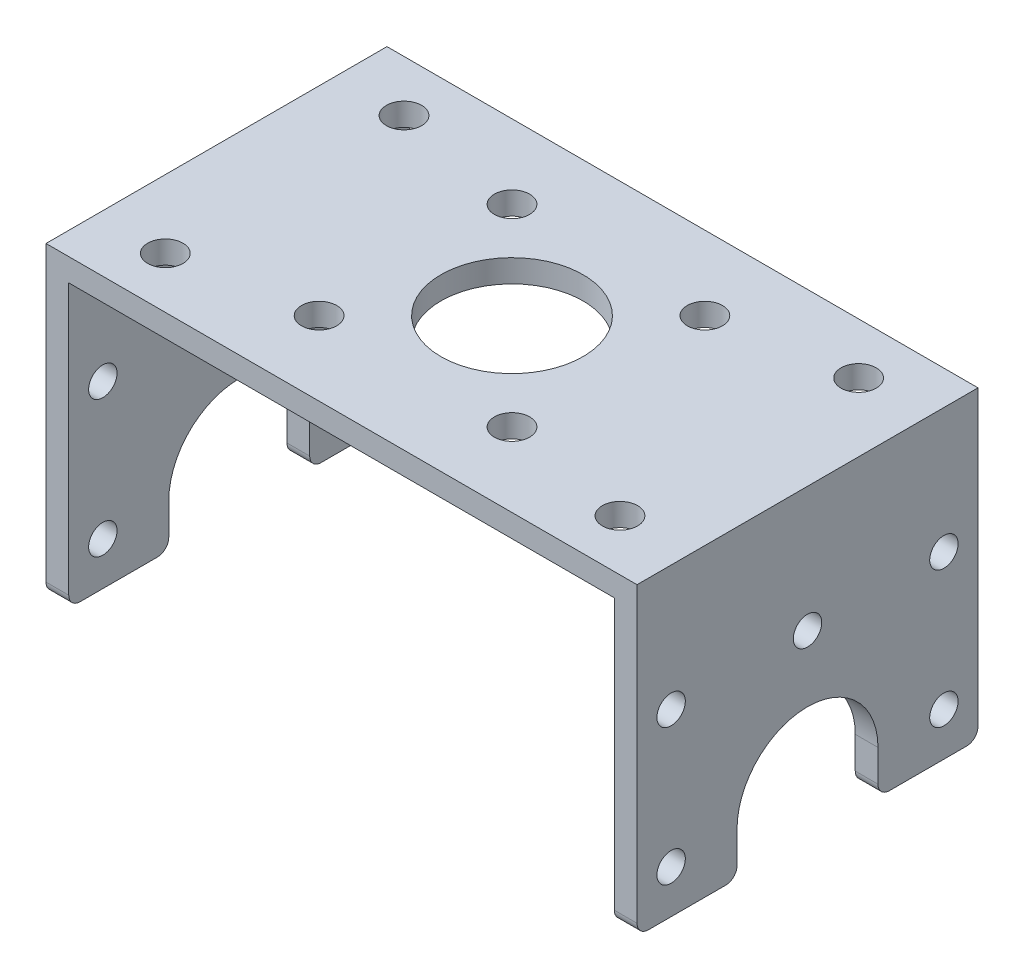
SolidWorks part; units mm, degrees
ref_plane "Plan de face" through (0, 0, 0) normal (0, 0, 1) x (1, 0, 0)
ref_plane "Plan de dessus" through (0, 0, 0) normal (0, 1, 0) x (1, 0, 0)
ref_plane "Plan de droite" through (0, 0, 0) normal (1, 0, 0) x (0, 0, -1)
sketch "Esquisse1" plane through (0, 0, 0) normal (0, 0, 1) x (1, 0, 0)
  line L0 (0, 0) -> (0, 26.8) construction
  line L1 (-26, 26.8) -> (26, 26.8)
  line L2 (26, 26.8) -> (26, 0)
  line L3 (26, 0) -> (24, 0)
  line L4 (24, 0) -> (24, 24.8)
  line L5 (24, 24.8) -> (-24, 24.8)
  line L6 (-24, 0) -> (-24, 24.8)
  line L7 (-26, 0) -> (-24, 0)
  line L8 (-26, 26.8) -> (-26, 0)
  point P9 (0, 24.8)
  dimension "D1" = 2
  dimension "D2" = 2
  dimension "D3" = 52
  dimension "D4" = 26.8
extrude "Boss.-Extru.1" add sketch "Esquisse1" along normal mid plane 30
sketch "Esquisse4" plane through (0, 26.8, 0) normal (0, 1, 0) x (1, 0, 0)
  line L0 (0, 0) -> (26, 0) construction
  line L1 (26, -15) -> (26, 15) construction
  line L2 (0, 0) -> (0, 15) construction
  line L3 (-8.4853, 8.4853) -> (8.4853, 8.4853) construction
  line L4 (-8.4853, 8.4853) -> (-8.4853, -8.4853) construction
  line L5 (-8.4853, -8.4853) -> (8.4853, -8.4853) construction
  line L6 (8.4853, 8.4853) -> (8.4853, -8.4853) construction
  line L7 (26, 15) -> (-26, 15) construction
  circle A0 centre (0, 0) radius 6.25
  circle A1 centre (0, 0) radius 12 construction
  circle A2 centre (-8.4853, 8.4853) radius 1.55
  circle A3 centre (8.4853, 8.4853) radius 1.55
  circle A4 centre (8.4853, -8.4853) radius 1.55
  circle A5 centre (-8.4853, -8.4853) radius 1.55
  circle A6 centre (20, 10.5) radius 1.55
  circle A7 centre (-20, 10.5) radius 1.55
  circle A8 centre (20, -10.5) radius 1.55
  circle A9 centre (-20, -10.5) radius 1.55
  dimension "D1" = 12.5
  dimension "D2" = 3.1
  dimension "D3" = 24
  dimension "D4" = 21
  dimension "D5" = 40
extrude "Enlèv. mat.-Extru.2" cut sketch "Esquisse4" against normal through all
sketch "Esquisse2" plane through (26, 0, 0) normal (1, 0, 0) x (0, 0, -1)
  line L0 (0, 3.8) -> (0, 15.8) construction
  line L1 (-6.2, 3.8) -> (-6.2, 0)
  line L2 (-15, 0) -> (15, 0) construction
  line L3 (6.2, 3.8) -> (6.2, 0)
  line L4 (0, 3.8) -> (0, 0) construction
  line L5 (-6.2, 0) -> (6.2, 0)
  line L6 (-12, 3.8) -> (-12, 15.8) construction
  line L7 (-12, 15.8) -> (0, 15.8) construction
  arc A0 (-6.2, 3.8) -> (6.2, 3.8) centre (0, 3.8) cw
  circle A1 centre (0, 3.8) radius 12 construction
  circle A2 centre (-12, 15.8) radius 1.25
  circle A3 centre (-12, 3.8) radius 1.25
  circle A4 centre (0, 15.8) radius 1.25
  circle A5 centre (12, 3.8) radius 1.25
  circle A6 centre (12, 15.8) radius 1.25
  point P3 (0, 10)
  dimension "D1" = 6.2
  dimension "D3" = 24
  dimension "D4" = 2.5
  dimension "D2" = 10
extrude "Enlèv. mat.-Extru.1" cut sketch "Esquisse2" against normal through all
fillet "Congé1" radius 1 8 edges at (25, 0, -15) (25, 0, -6.2) (25, 0, 6.2) (25, 0, 15) (-25, 0, -15) (-25, 0, -6.2) (-25, 0, 6.2) (-25, 0, 15)
equation "\"D2@Esquisse1\"=\"D1@Esquisse1\""
